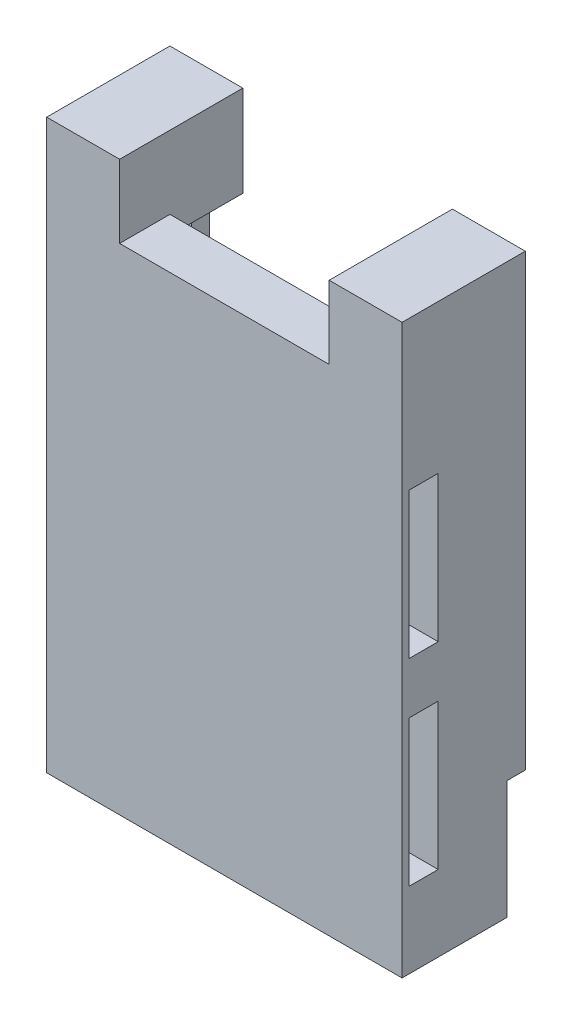
SolidWorks part; units mm, degrees
ref_plane "Front Plane" through (0, 0, 0) normal (0, 0, 1) x (1, 0, 0)
ref_plane "Top Plane" through (0, 0, 0) normal (0, 1, 0) x (1, 0, 0)
ref_plane "Right Plane" through (0, 0, 0) normal (1, 0, 0) x (0, 0, -1)
sketch "Sketch1" plane through (0, 0, 0) normal (0, 1, 0) x (1, 0, 0)
  line L0 (0, 0) -> (0, 60.439) construction
  line L1 (0, 0) -> (86.9706, 0) construction
  line L2 (-30.9499, -3.4771) -> (30.9499, -3.4771)
  line L4 (27.7749, 5.2859) -> (-27.7749, 5.2859)
  line L7 (-30.9499, 17.9859) -> (-24.0411, 17.9859)
  line L8 (-24.0411, 17.9859) -> (-24.0411, 14.8109)
  line L9 (-24.0411, 14.8109) -> (-27.7749, 14.8109)
  line L10 (-27.7749, 14.8109) -> (-27.7749, 5.2859)
  line L11 (24.0411, 14.8109) -> (27.7749, 14.8109)
  line L12 (27.7749, 14.8109) -> (27.7749, 5.2859)
  line L14 (30.9499, 17.9859) -> (24.0411, 17.9859)
  line L15 (24.0411, 17.9859) -> (24.0411, 14.8109)
  line L16 (-30.9499, 17.9859) -> (-30.9499, -3.4771)
  line L17 (30.9499, 17.9859) -> (30.9499, -3.4771)
  dimension "D1" = 61.8998
  dimension "D2" = 3.175
  dimension "D3" = 8.763
  dimension "D4" = 6.9088
  dimension "D5" = 27.7749
  dimension "D6" = 9.525
extrude "Boss-Extrude1" add sketch "Sketch1" along normal blind 83.0326 contours L14 L15 L11 L12 L4 L10 L9 L8 L7 L16 L2 L17
sketch "Sketch6" plane through (0, 83.0326, 0) normal (0, 1, 0) x (1, 0, 0)
  line L0 (-30.9499, 17.9859) -> (-30.9499, -3.4771)
  line L1 (-30.9499, -3.4771) -> (30.9499, -3.4771)
  line L2 (30.9499, -3.4771) -> (30.9499, 17.9859)
  line L3 (30.9499, 17.9859) -> (-30.9499, 17.9859)
extrude "Boss-Extrude3" add sketch "Sketch6" along normal blind 3.175
sketch "Sketch7" plane through (0, 83.0326, 0) normal (0, -1, 0) x (1, 0, 0)
  line L0 (0, -5.2859) -> (0, -14.8109) construction
  line L1 (27.7749, -5.2859) -> (-27.7749, -5.2859) construction
  line L2 (-8.2677, -5.2859) -> (-8.2677, -14.8109)
  line L3 (8.2677, -5.2859) -> (8.2677, -14.8109)
  line L4 (8.2677, -14.8109) -> (-8.2677, -14.8109)
  line L5 (8.2677, -5.2859) -> (-8.2677, -5.2859)
  dimension "D1" = 9.525
  dimension "D2" = 8.2677
  dimension "D3" = 8.2677
extrude "Cut-Extrude2" cut sketch "Sketch7" against normal through all
sketch "Sketch8" plane through (-30.9499, 0, 0) normal (-1, 0, 0) x (0, 0, 1)
  line L0 (-17.9859, 43.1038) -> (3.4771, 43.1038) construction
  line L1 (-17.9859, 86.2076) -> (-17.9859, 0) construction
  line L2 (3.4771, 86.2076) -> (3.4771, 0) construction
  line L4 (2.2655, 13.224) -> (2.2655, 38.624)
  line L6 (-0.4599, 43.1038) -> (-0.4599, 24.0538) construction
  line L7 (2.2655, 13.224) -> (-2.8145, 13.224)
  line L8 (2.2655, 72.9836) -> (-2.8145, 72.9836)
  line L9 (2.2655, 72.9836) -> (2.2655, 47.5836)
  line L10 (2.2655, 47.5836) -> (-2.8145, 47.5836)
  line L11 (-2.8145, 72.9836) -> (-2.8145, 47.5836)
  line L14 (-2.8145, 13.224) -> (-2.8145, 38.624)
  line L15 (2.2655, 38.624) -> (-2.8145, 38.624)
  point P8 (2.2655, 60.2836)
  point P21 (2.2655, 25.924)
  dimension "D3" = 5.08
  dimension "D4" = 25.4
extrude "Cut-Extrude3" cut sketch "Sketch8" against normal through all contours L8 L11 L10 L9 | L4 L15 L14 L7
sketch "Sketch14" plane through (0, 0, 0) normal (0, -1, 0) x (1, 0, 0)
  line L0 (-27.7749, -5.2859) -> (-30.9499, -5.2859) construction
  line L1 (-30.9499, -17.9859) -> (-30.9499, 3.4771) construction
sketch "Sketch15" plane through (0, 0, -17.9859) normal (0, 0, -1) x (-1, 0, 0)
  line L0 (-30.9499, 0) -> (30.9499, 0)
  line L1 (-30.9499, 20.6324) -> (30.9499, 20.6324)
  line L2 (-30.9499, 20.6324) -> (-30.9499, 0)
  line L3 (30.9499, 0) -> (30.9499, 20.6324)
  dimension "D1" = 20.6324
extrude "Cut-Extrude4" cut sketch "Sketch15" against normal blind 3.175
sketch "Sketch16" plane through (0, 86.2076, 0) normal (0, 1, 0) x (1, 0, 0)
  line L1 (30.9499, 17.9859) -> (-30.9499, 17.9859) construction
  line L2 (0, 17.9859) -> (0, 5.2859) construction
  line L3 (8.2677, 5.2859) -> (-8.2677, 5.2859) construction
  line L6 (-18.2499, 17.9859) -> (-18.2499, 5.2859)
  line L7 (-18.2499, 5.2859) -> (18.2499, 5.2859)
  line L8 (18.2499, 5.2859) -> (18.2499, 17.9859)
  line L9 (-18.2499, 17.9859) -> (18.2499, 17.9859)
extrude "Cut-Extrude5" cut sketch "Sketch16" against normal blind 3.175
sketch "Sketch17" plane through (0, 86.2076, 0) normal (0, 1, 0) x (1, 0, 0)
  line L0 (-30.9499, 17.9859) -> (-30.9499, -3.4771)
  line L1 (-30.9499, -3.4771) -> (-18.2499, -3.4771)
  line L2 (-30.9499, -3.4771) -> (30.9499, -3.4771) construction
  line L3 (-18.2499, -3.4771) -> (-18.2499, 17.9859)
  line L4 (-18.2499, 17.9859) -> (-30.9499, 17.9859)
  line L5 (18.2499, 17.9859) -> (18.2499, -3.4771)
  line L6 (18.2499, -3.4771) -> (30.9499, -3.4771)
  line L7 (30.9499, -3.4771) -> (30.9499, 17.9859)
  line L8 (30.9499, 17.9859) -> (18.2499, 17.9859)
extrude "Boss-Extrude4" add sketch "Sketch17" along normal blind 12.7
equation "\"1.0921.1120754in\"=1.11208"
equation "\"0.0625in..6690\"=0.0625"
